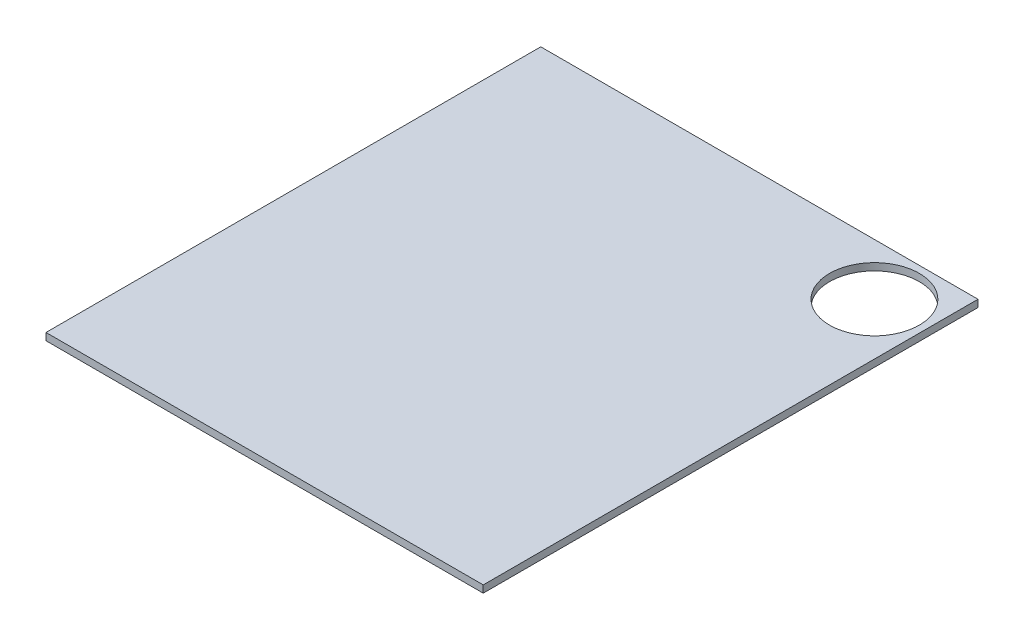
SolidWorks part; units mm, degrees
material "PPE"
ref_plane "Front Plane" through (0, 0, 0) normal (0, 0, 1) x (1, 0, 0)
ref_plane "Top Plane" through (0, 0, 0) normal (0, 1, 0) x (1, 0, 0)
ref_plane "Right Plane" through (0, 0, 0) normal (1, 0, 0) x (0, 0, -1)
sketch "Sketch1" plane through (0, 0, 0) normal (0, 1, 0) x (1, 0, 0)
  line L0 (106, 170) -> (106, 215)
  line L1 (-190, -215) -> (190, -215)
  line L2 (-190, -215) -> (-190, 215)
  line L3 (-190, 215) -> (190, 215)
  line L4 (190, -215) -> (190, 215)
  line L5 (-190, -215) -> (190, 215) construction
  line L6 (-190, 215) -> (190, -215) construction
  line L7 (184, 170) -> (184, 215)
  line L8 (184, 215) -> (106, 215)
  circle A0 centre (145, 170) radius 39
  point P0 (0, 0)
  dimension "D3" = 78
  dimension "D1" = 430
  dimension "D2" = 380
  dimension "D4" = 45
  dimension "D5" = 45
extrude "Boss-Extrude1" add sketch "Sketch1" along normal blind 6.25 contours A0 L7 L3 L0 | A0 L0 L3 L2 L1 L4 L7
